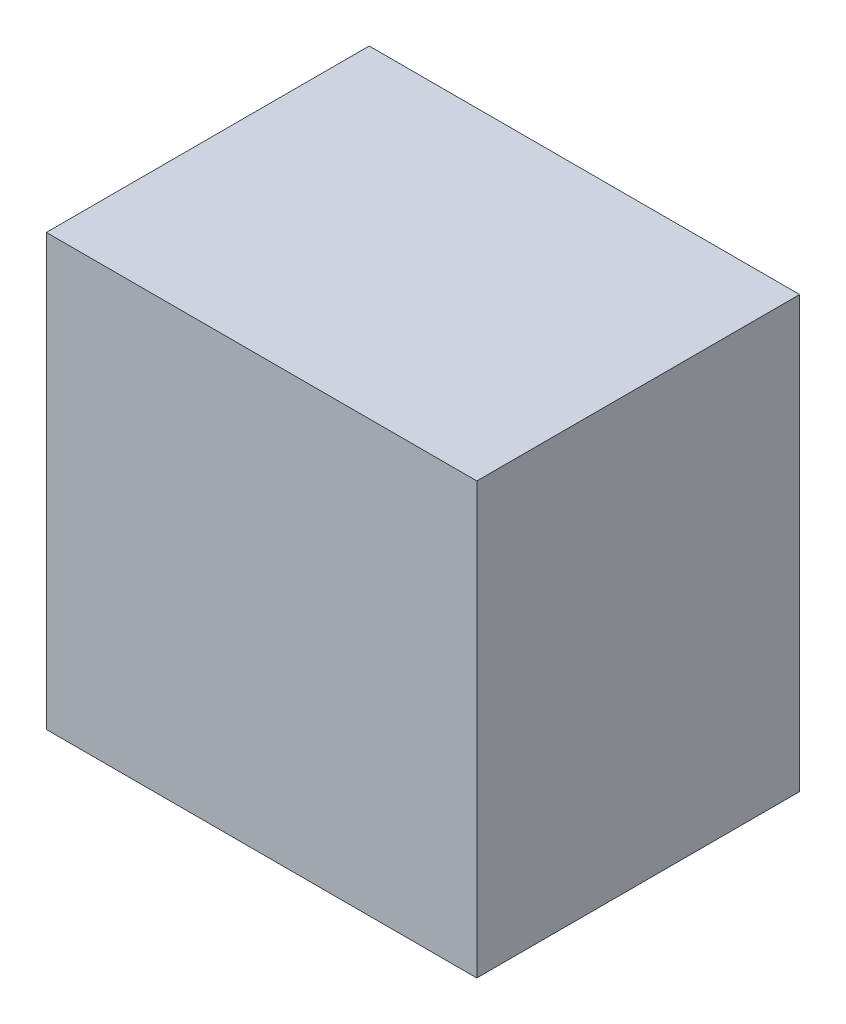
SolidWorks part; units mm, degrees
ref_plane "Front Plane" through (0, 0, 0) normal (0, 0, 1) x (1, 0, 0)
ref_plane "Top Plane" through (0, 0, 0) normal (0, 1, 0) x (1, 0, 0)
ref_plane "Right Plane" through (0, 0, 0) normal (1, 0, 0) x (0, 0, -1)
sketch "Sketch1" plane through (0, 0, 0) normal (0, 0, 1) x (1, 0, 0)
  line L0 (25.4, 25.4) -> (25.4, -25.4)
  line L3 (-25.4, -25.4) -> (25.4, -25.4)
  line L4 (-25.4, -25.4) -> (-25.4, 25.4)
  line L5 (-25.4, 25.4) -> (25.4, 25.4)
  line L8 (0, 25.4) -> (0, -25.4) construction
  line L9 (-25.4, 0) -> (19.5286, 0) construction
  point P0 (0, 0)
  point P2 (0, 0)
  dimension "D1" = 50.8
extrude "Boss-Extrude1" add sketch "Sketch1" along normal blind 38.1
